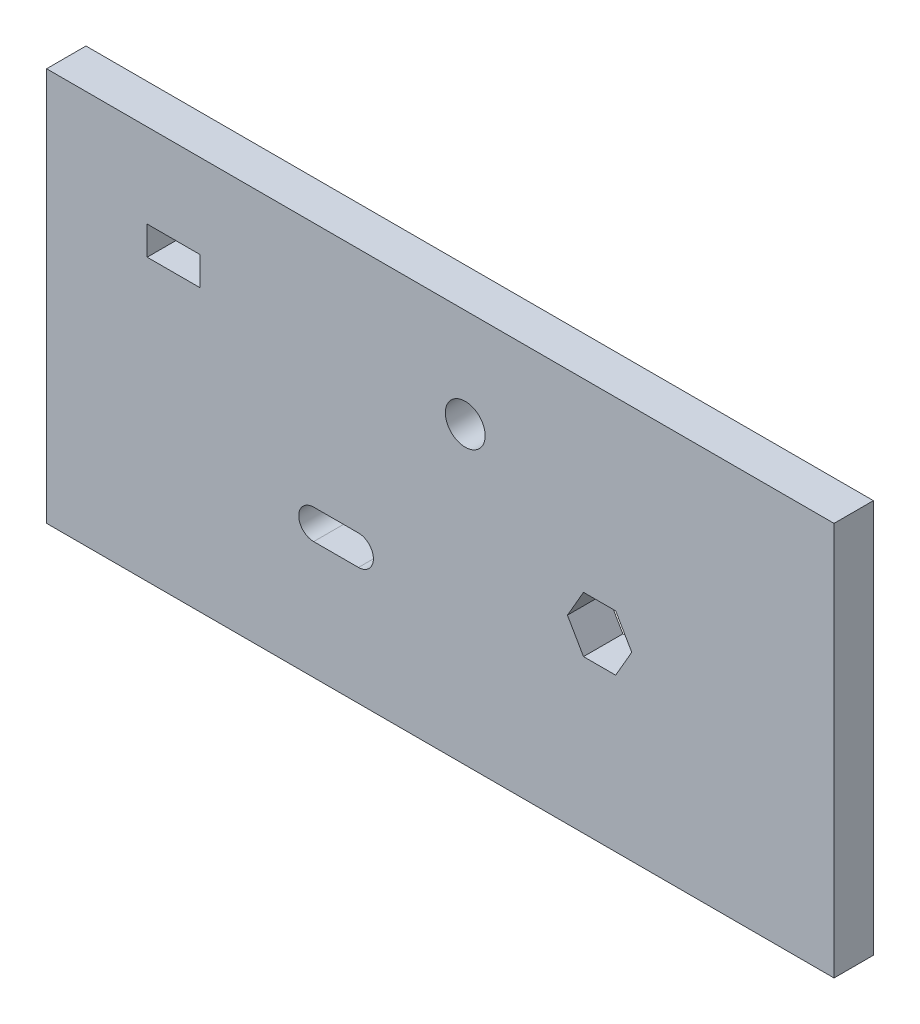
SolidWorks part; units mm, degrees
ref_plane "Front Plane" through (0, 0, 0) normal (0, 0, 1) x (1, 0, 0)
ref_plane "Top Plane" through (0, 0, 0) normal (0, 1, 0) x (1, 0, 0)
ref_plane "Right Plane" through (0, 0, 0) normal (1, 0, 0) x (0, 0, -1)
sketch "Sketch1" plane through (0, 0, 0) normal (0, 0, 1) x (1, 0, 0)
  line L1 (0, 0) -> (-200, 0)
  line L2 (0, 0) -> (0, 100)
  line L3 (0, 100) -> (-200, 100)
  line L4 (-200, 0) -> (-200, 100)
  dimension "D1" = 200
  dimension "D2" = 100
extrude "Boss-Extrude1" add sketch "Sketch1" along normal blind 10
sketch "Sketch2" plane through (0, 0, 10) normal (0, 0, 1) x (1, 0, 0)
  line L0 (-132.1633, 33.7005) -> (-120.7894, 33.7005) construction
  line L1 (-174.4506, 78.6126) -> (-161.0353, 78.6126)
  line L2 (-174.4506, 78.6126) -> (-174.4506, 71.3217)
  line L3 (-174.4506, 71.3217) -> (-161.0353, 71.3217)
  line L4 (-161.0353, 78.6126) -> (-161.0353, 71.3217)
  line L5 (-132.1633, 37.4918) -> (-120.7894, 37.4918)
  line L6 (-132.1633, 29.9092) -> (-120.7894, 29.9092)
  line L8 (-51.3798, 45.9492) -> (-55.4628, 53.0211)
  line L9 (-55.4628, 53.0211) -> (-63.6286, 53.0211)
  line L10 (-63.6286, 53.0211) -> (-67.7115, 45.9492)
  line L11 (-67.7115, 45.9492) -> (-63.6286, 38.8774)
  line L12 (-63.6286, 38.8774) -> (-55.4628, 38.8774)
  line L13 (-55.4628, 38.8774) -> (-51.3798, 45.9492)
  circle A0 centre (-93.6672, 74.9671) radius 5.0534
  arc A1 (-132.1633, 37.4918) -> (-132.1633, 29.9092) centre (-132.1633, 33.7005) ccw
  arc A2 (-120.7894, 29.9092) -> (-120.7894, 37.4918) centre (-120.7894, 33.7005) ccw
  circle A3 centre (-59.5457, 45.9492) radius 7.0718 construction
  point P8 (-126.4764, 33.7005)
extrude "Cut-Extrude1" cut sketch "Sketch2" against normal blind 10
